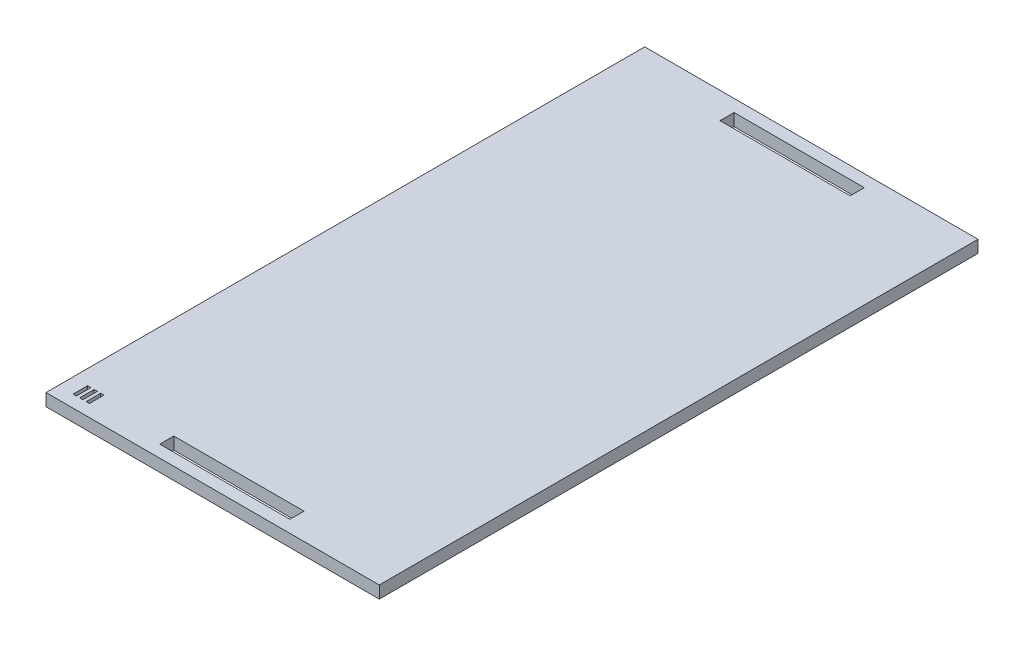
SolidWorks part; units mm, degrees
ref_plane "Front Plane" through (0, 0, 0) normal (0, 0, 1) x (1, 0, 0)
ref_plane "Top Plane" through (0, 0, 0) normal (0, 1, 0) x (1, 0, 0)
ref_plane "Right Plane" through (0, 0, 0) normal (1, 0, 0) x (0, 0, -1)
sketch "Sketch1" plane through (0, 0, 0) normal (0, 1, 0) x (1, 0, 0)
  line L0 (-40.6471, 66.4972) -> (40.6471, 66.4972) construction
  line L1 (40.6471, -73.025) -> (-40.6471, -73.025)
  line L2 (40.6471, -73.025) -> (40.6471, 73.025)
  line L3 (40.6471, 73.025) -> (-40.6471, 73.025)
  line L4 (-40.6471, -73.025) -> (-40.6471, 73.025)
  line L5 (40.6471, -73.025) -> (-40.6471, 73.025) construction
  line L6 (40.6471, 73.025) -> (-40.6471, -73.025) construction
  line L7 (-40.6471, -66.4972) -> (40.6471, -66.4972) construction
  line L8 (-40.6471, 66.4972) -> (-40.6471, -66.4972) construction
  line L9 (40.6471, 66.4972) -> (40.6471, -66.4972) construction
  line L10 (0, 66.6242) -> (0, -66.6242) construction
  line L11 (-15.875, 70.0532) -> (15.875, 70.0532)
  line L12 (-15.875, 70.0532) -> (-15.875, 66.6242)
  line L13 (-15.875, 66.6242) -> (15.875, 66.6242)
  line L14 (15.875, 70.0532) -> (15.875, 66.6242)
  line L15 (-15.875, -66.6242) -> (15.875, -66.6242)
  line L16 (-15.875, -66.6242) -> (-15.875, -70.0532)
  line L17 (-15.875, -70.0532) -> (15.875, -70.0532)
  line L18 (15.875, -66.6242) -> (15.875, -70.0532)
  line L19 (-40.6471, -70.0532) -> (40.6471, -70.0532) construction
  line L20 (-36.2199, -68.2752) -> (-35.4261, -68.2752) construction
  line L21 (-37.0136, -66.4972) -> (-36.2199, -66.4972)
  line L22 (-37.0136, -66.4972) -> (-37.0136, -70.0532)
  line L23 (-37.0136, -70.0532) -> (-36.2199, -70.0532)
  line L24 (-36.2199, -66.4972) -> (-36.2199, -70.0532)
  line L25 (-35.4261, -70.0532) -> (-34.6324, -70.0532)
  line L26 (-35.4261, -70.0532) -> (-35.4261, -66.4972)
  line L27 (-35.4261, -66.4972) -> (-34.6324, -66.4972)
  line L28 (-34.6324, -70.0532) -> (-34.6324, -66.4972)
  line L29 (-34.6324, -68.2752) -> (-33.8386, -68.2752) construction
  line L30 (-33.8386, -66.4972) -> (-33.0449, -66.4972)
  line L31 (-33.8386, -66.4972) -> (-33.8386, -70.0532)
  line L32 (-33.8386, -70.0532) -> (-33.0449, -70.0532)
  line L33 (-33.0449, -66.4972) -> (-33.0449, -70.0532)
  point P0 (0, 0)
  point P10 (40.6471, 0)
  point P11 (40.6471, 0)
  point P16 (0, 66.6242)
  point P17 (0, 0)
  dimension "D1" = 81.2943
  dimension "D2" = 146.05
  dimension "D3" = 132.9944
  dimension "D4" = 3.429
  dimension "D5" = 31.75
  dimension "D6" = 0.254
  dimension "D7" = 0.7937
extrude "Boss-Extrude1" add sketch "Sketch1" along normal blind 2.9972 contours L4 L1 L2 L3 L11 L14 L13 L12 L15 L18 L17 L16
